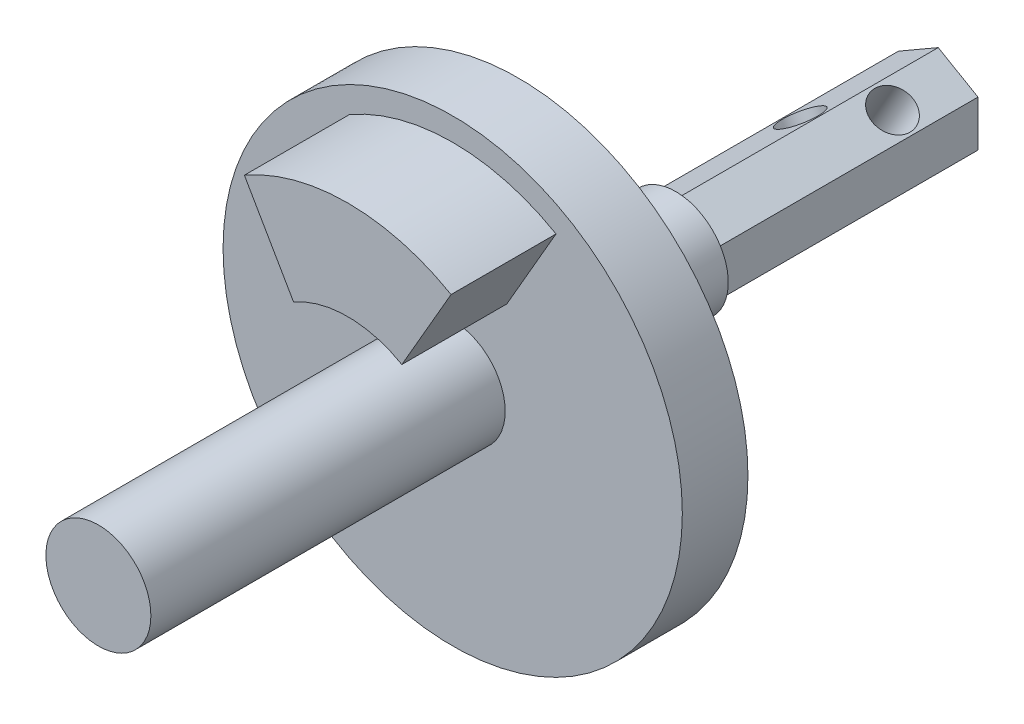
SolidWorks part; units mm, degrees
ref_plane "Front Plane" through (0, 0, 0) normal (0, 0, 1) x (1, 0, 0)
ref_plane "Top Plane" through (0, 0, 0) normal (0, 1, 0) x (1, 0, 0)
ref_plane "Right Plane" through (0, 0, 0) normal (1, 0, 0) x (0, 0, -1)
sketch "Sketch1" plane through (0, 0, 0) normal (0, 0, 1) x (1, 0, 0)
  circle A0 centre (0, 0) radius 17.5
  dimension "D1" = 35
extrude "Boss-Extrude1" add sketch "Sketch1" along normal mid plane 5
sketch "Sketch2" plane through (0, 0, 2.5) normal (0, 0, 1) x (1, 0, 0)
  line L3 (0, 0) -> (0, 11) construction
  line L4 (7.875, 13.6399) -> (4.125, 7.1447)
  line L5 (-4.125, 7.1447) -> (-7.875, 13.6399)
  arc A1 (4.125, 7.1447) -> (-4.125, 7.1447) centre (0, 0) ccw
  arc A6 (-7.875, 13.6399) -> (7.875, 13.6399) centre (0, 0) cw
  circle A7 centre (0, 0) radius 17.5 construction
  dimension "D2" = 7.5
  dimension "D3" = 1.75
  dimension "D1" = 30
extrude "Boss-Extrude2" add sketch "Sketch2" along normal blind 8
sketch "Sketch3" plane through (0, 0, 2.5) normal (0, 0, 1) x (1, 0, 0)
  circle A0 centre (0, 0) radius 4
extrude "Boss-Extrude3" add sketch "Sketch3" along normal blind 27
sketch "Sketch7" plane through (0, 0, -2.5) normal (0, 0, -1) x (-1, 0, 0)
  circle A0 centre (0, 0) radius 4
extrude "Boss-Extrude4" add sketch "Sketch7" along normal blind 12
sketch "Sketch9" plane through (0, 0, -14.5) normal (0, 0, -1) x (-1, 0, 0)
  line L11 (0, 3.5) -> (-3.0311, 1.75)
  line L12 (-3.0311, 1.75) -> (-3.0311, -1.75)
  line L13 (-3.0311, -1.75) -> (0, -3.5)
  line L14 (0, -3.5) -> (3.0311, -1.75)
  line L15 (3.0311, -1.75) -> (3.0311, 1.75)
  line L16 (3.0311, 1.75) -> (0, 3.5)
  point P5 (0, 0)
  point P6 (0, 0)
  point P8 (0, 0)
  point P11 (0, 0)
  point P13 (0, 0)
  point P15 (0, 0)
extrude "Boss-Extrude5" add sketch "Sketch9" along normal blind 20
sketch "Sketch10" plane through (-1.5155, -2.625, 0) normal (-0.5, -0.866, 0) x (0.866, -0.5, 0)
  line L0 (0, -34.5) -> (0, -29.5) construction
  line L1 (1.75, -34.5) -> (-1.75, -34.5) construction
  circle A0 centre (0, -29.5) radius 1.55
extrude "Cut-Extrude1" cut sketch "Sketch10" against normal blind 6.1
sketch "Sketch11" plane through (1.5155, -2.625, 0) normal (-0.5, 0.866, 0) x (0, 0, 1)
  line L0 (-34.5, 0) -> (-25.5, 0) construction
  line L3 (-34.5, -1.75) -> (-34.5, 1.75) construction
  circle A1 centre (-25.5, 0) radius 1.55
extrude "Cut-Extrude4" cut sketch "Sketch11" along normal blind 6.1
